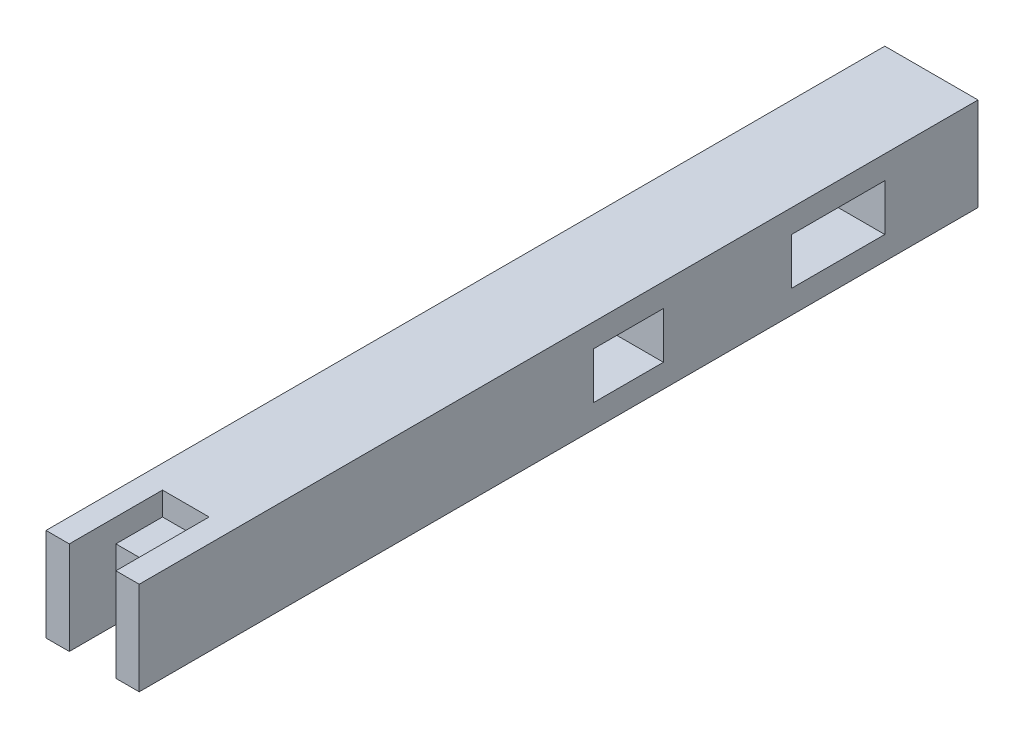
SolidWorks part; units mm, degrees
ref_plane "Front Plane" through (0, 0, 0) normal (0, 0, 1) x (1, 0, 0)
ref_plane "Top Plane" through (0, 0, 0) normal (0, 1, 0) x (1, 0, 0)
ref_plane "Right Plane" through (0, 0, 0) normal (1, 0, 0) x (0, 0, -1)
sketch "Sketch1" plane through (0, 0, 0) normal (0, 0, 1) x (1, 0, 0)
  line L1 (-50.8, -50.8) -> (50.8, -50.8)
  line L2 (-50.8, -50.8) -> (-50.8, 50.8)
  line L3 (-50.8, 50.8) -> (50.8, 50.8)
  line L4 (50.8, -50.8) -> (50.8, 50.8)
  line L5 (-50.8, -50.8) -> (50.8, 50.8) construction
  line L6 (-50.8, 50.8) -> (50.8, -50.8) construction
  point P0 (0, 0)
  dimension "D1" = 101.6
  dimension "D2" = 101.6
extrude "Boss-Extrude1" add sketch "Sketch1" along normal blind 914.4
sketch "Sketch2" plane through (50.8, 0, 0) normal (1, 0, 0) x (0, 0, -1)
  line L1 (-203.2, -25.4) -> (-101.6, -25.4)
  line L2 (-203.2, -25.4) -> (-203.2, 25.4)
  line L3 (-203.2, 25.4) -> (-101.6, 25.4)
  line L4 (-101.6, -25.4) -> (-101.6, 25.4)
  line L5 (-203.2, -25.4) -> (-101.6, 25.4) construction
  line L6 (-203.2, 25.4) -> (-101.6, -25.4) construction
  point P0 (-152.4, 0)
  dimension "D1" = 101.6
  dimension "D2" = 50.8
  dimension "D3" = 152.4
  dimension "D4" = 0
extrude "Cut-Extrude1" cut sketch "Sketch2" against normal through all both
sketch "Sketch3" plane through (0, 0, 914.4) normal (0, 0, 1) x (1, 0, 0)
  line L0 (50.8, 50.8) -> (-50.8, 50.8) construction
  line L1 (-25.4, -50.8) -> (25.4, -50.8)
  line L2 (-25.4, -50.8) -> (-25.4, 50.8)
  line L3 (-25.4, 50.8) -> (25.4, 50.8)
  line L4 (25.4, -50.8) -> (25.4, 50.8)
  line L5 (-25.4, -50.8) -> (25.4, 50.8) construction
  line L6 (-25.4, 50.8) -> (25.4, -50.8) construction
  point P0 (0, 0)
  dimension "D1" = 50.8
extrude "Cut-Extrude2" cut sketch "Sketch3" against normal blind 50.8
sketch "Sketch4" plane through (0, 0, 863.6) normal (0, 0, 1) x (1, 0, 0)
  line L0 (25.4, -50.8) -> (25.4, 50.8) construction
  line L1 (-25.4, 50.8) -> (25.4, 50.8)
  line L2 (-25.4, 50.8) -> (-25.4, 25.4)
  line L3 (-25.4, 25.4) -> (25.4, 25.4)
  line L4 (25.4, 50.8) -> (25.4, 25.4)
  line L5 (25.4, -50.8) -> (25.4, 50.8) construction
  line L6 (-25.4, -50.8) -> (25.4, -50.8)
  line L7 (-25.4, -50.8) -> (-25.4, -25.4)
  line L8 (-25.4, -25.4) -> (25.4, -25.4)
  line L9 (25.4, -50.8) -> (25.4, -25.4)
  dimension "D1" = 25.4
  dimension "D2" = 25.4
extrude "Cut-Extrude3" cut sketch "Sketch4" against normal blind 50.8
sketch "Sketch5" plane through (-50.8, 0, 0) normal (-1, 0, 0) x (0, 0, 1)
  line L0 (203.2, 0) -> (381, 0) construction
  line L1 (203.2, 25.4) -> (203.2, -25.4) construction
  line L3 (419.1, 25.4) -> (342.9, 25.4)
  line L4 (419.1, 25.4) -> (419.1, -25.4)
  line L5 (419.1, -25.4) -> (342.9, -25.4)
  line L6 (342.9, 25.4) -> (342.9, -25.4)
  line L7 (419.1, 25.4) -> (342.9, -25.4) construction
  line L8 (419.1, -25.4) -> (342.9, 25.4) construction
  dimension "D1" = 177.8
  dimension "D2" = 50.8
  dimension "D3" = 76.2
extrude "Cut-Extrude4" cut sketch "Sketch5" against normal through all
